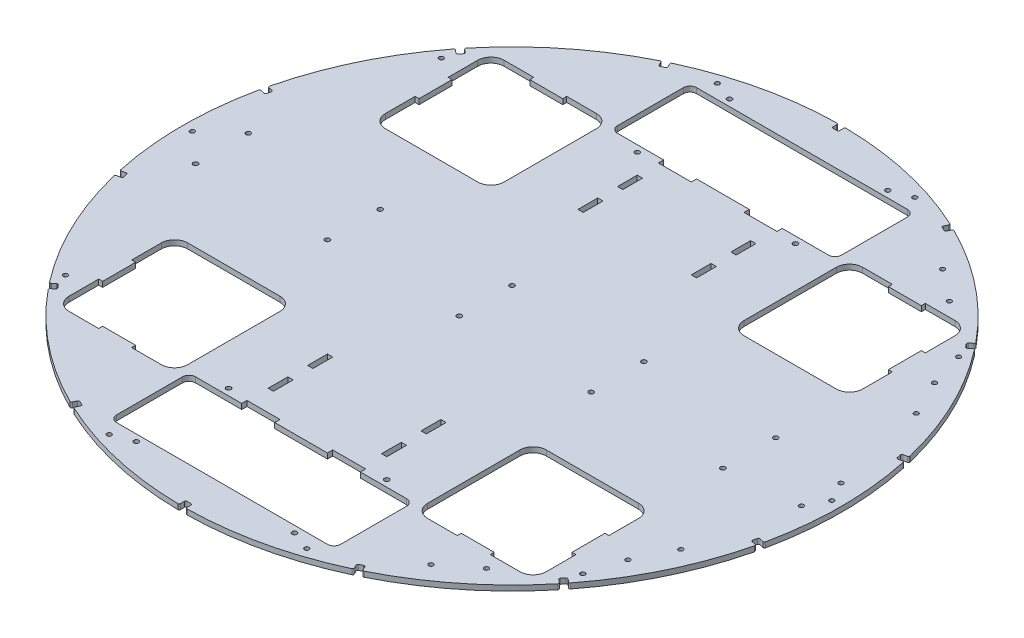
SolidWorks part; units mm, degrees
ref_plane "Front Plane" through (0, 0, 0) normal (0, 0, 1) x (1, 0, 0)
ref_plane "Top Plane" through (0, 0, 0) normal (0, 1, 0) x (1, 0, 0)
ref_plane "Right Plane" through (0, 0, 0) normal (1, 0, 0) x (0, 0, -1)
sketch "Sketch1" plane through (0, 0, 0) normal (0, 1, 0) x (1, 0, 0)
  circle A0 centre (0, 0) radius 250
extrude "Boss-Extrude1" add sketch "Sketch1" along normal blind 4
sketch "Sketch2" plane through (0, 4, 0) normal (0, 1, 0) x (1, 0, 0)
  line L0 (0, -250) -> (0, 250) construction
  line L1 (80, 220) -> (-80, 220)
  line L2 (85, 215) -> (85, 165)
  line L3 (80, 160) -> (-80, 160)
  line L4 (-85, 215) -> (-85, 165)
  line L5 (85, 220) -> (-85, 160) construction
  line L6 (85, 160) -> (-85, 220) construction
  line L7 (-55, 0) -> (55, 0) construction
  line L8 (85, -215) -> (85, -165)
  line L9 (80, -160) -> (-80, -160)
  line L10 (-85, -215) -> (-85, -165)
  line L11 (80, -220) -> (-80, -220)
  circle A0 centre (0, 0) radius 250 construction
  arc A1 (-80, 160) -> (-85, 165) centre (-80, 165) cw
  arc A2 (80, 160) -> (85, 165) centre (80, 165) ccw
  arc A3 (85, 215) -> (80, 220) centre (80, 215) ccw
  arc A4 (-80, 220) -> (-85, 215) centre (-80, 215) ccw
  arc A5 (-85, -215) -> (-80, -220) centre (-80, -215) ccw
  arc A6 (80, -220) -> (85, -215) centre (80, -215) ccw
  arc A7 (85, -165) -> (80, -160) centre (80, -165) ccw
  arc A8 (-80, -160) -> (-85, -165) centre (-80, -165) ccw
  point P0 (0, 190)
  point P33 (-85, -220)
  point P36 (85, -220)
  point P39 (85, -160)
  point P42 (-85, -160)
  dimension "D4" = 5
  dimension "D5" = 5
  dimension "D1" = 170
  dimension "D2" = 190
  dimension "D3" = 60
extrude "Cut-Extrude1" cut sketch "Sketch2" against normal blind 10
sketch "Sketch3" plane through (0, 4, 0) normal (0, 1, 0) x (1, 0, 0)
  line L0 (45, 160) -> (-45, 160)
  line L1 (-80, 160) -> (80, 160) construction
  line L2 (0, -2.2) -> (0, 2.2) construction
  line L3 (-45, 160) -> (-20, 160)
  line L4 (-45, 160) -> (-45, 156)
  line L5 (-45, 156) -> (-20, 156)
  line L6 (-20, 160) -> (-20, 156)
  line L7 (20, 160) -> (20, 156)
  line L8 (45, 156) -> (20, 156)
  line L9 (45, 160) -> (45, 156)
  line L10 (45, 160) -> (20, 160)
  line L11 (-2.2, 0) -> (2.2, 0) construction
  line L12 (45, -160) -> (20, -160)
  line L13 (45, -160) -> (45, -156)
  line L14 (45, -156) -> (20, -156)
  line L15 (20, -160) -> (20, -156)
  line L16 (-20, -160) -> (-20, -156)
  line L17 (-45, -156) -> (-20, -156)
  line L18 (-45, -160) -> (-45, -156)
  line L19 (-45, -160) -> (-20, -160)
  line L20 (45, -160) -> (-45, -160)
  point P5 (0, 160)
  point P24 (0, -160)
  line M7 (80, 160) -> (-80, 160)
  line M10 (-80, -160) -> (80, -160)
  dimension "D2" = 4
  dimension "D3" = 25
extrude "Cut-Extrude2" cut sketch "Sketch3" against normal blind 5 contours L6 L0 L4 L5 | L9 L7 L8 M7 | L18 L16 L17 M10 | L15 L13 L14 M10
sketch "Sketch4" plane through (0, 4, 0) normal (0, 1, 0) x (1, 0, 0)
  line L0 (45, 160) -> (-45, 160)
  line L3 (80, 220) -> (-80, 220) construction
  line L4 (45, 160) -> (80, 160) construction
  line L5 (45, 140) -> (41, 140)
  line L6 (45, 140) -> (45, 125)
  line L7 (45, 125) -> (41, 125)
  line L8 (41, 140) -> (41, 125)
  line L9 (0, -2.2) -> (0, 2.2) construction
  line L10 (41, 110) -> (45, 110)
  line L11 (41, 110) -> (41, 95)
  line L12 (41, 95) -> (45, 95)
  line L13 (45, 110) -> (45, 95)
  line L14 (-45, 110) -> (-45, 95)
  line L15 (-41, 95) -> (-45, 95)
  line L16 (-41, 110) -> (-41, 95)
  line L17 (-41, 110) -> (-45, 110)
  line L18 (-41, 140) -> (-41, 125)
  line L19 (-45, 125) -> (-41, 125)
  line L20 (-45, 140) -> (-45, 125)
  line L21 (-45, 140) -> (-41, 140)
  line L22 (-2.2, 0) -> (2.2, 0) construction
  line L23 (-45, -140) -> (-41, -140)
  line L24 (-45, -140) -> (-45, -125)
  line L25 (-45, -125) -> (-41, -125)
  line L26 (-41, -140) -> (-41, -125)
  line L27 (-41, -110) -> (-45, -110)
  line L28 (-41, -110) -> (-41, -95)
  line L29 (-41, -95) -> (-45, -95)
  line L30 (-45, -110) -> (-45, -95)
  line L31 (45, -110) -> (45, -95)
  line L32 (41, -95) -> (45, -95)
  line L33 (41, -110) -> (41, -95)
  line L34 (41, -110) -> (45, -110)
  line L35 (41, -140) -> (41, -125)
  line L36 (45, -125) -> (41, -125)
  line L37 (45, -140) -> (45, -125)
  line L38 (45, -140) -> (41, -140)
  point P3 (0, 160)
  point P5 (0, 220)
  point P16 (45, 132.5)
  point P17 (45, 102.5)
  dimension "D1" = 0
  dimension "D2" = 4
  dimension "D3" = 0
  dimension "D4" = 90
  dimension "D5" = 15
  dimension "D6" = 20
  dimension "D7" = 15
  dimension "D8" = 4
  dimension "D9" = 30
extrude "Cut-Extrude3" cut sketch "Sketch4" against normal blind 20 contours L5 L8 L7 L6 | L13 L10 L11 L12 | L21 L20 L19 L18 | L16 L17 L14 L15 | L30 L27 L28 L29 | L23 L26 L25 L24 | L33 L34 L31 L32 | L38 L37 L36 L35
sketch "Sketch7" plane through (0, 4, 0) normal (0, 1, 0) x (1, 0, 0)
  line L0 (0, -2.2) -> (0, 2.2) construction
  line L1 (-101, 75) -> (-171, 75)
  line L2 (-91, 85) -> (-91, 155)
  line L3 (-101, 165) -> (-171, 165)
  line L4 (-181, 85) -> (-181, 155)
  line L5 (-91, 75) -> (-181, 165) construction
  line L6 (-91, 165) -> (-181, 75) construction
  line L7 (91, 165) -> (181, 75) construction
  line L8 (91, 75) -> (181, 165) construction
  line L9 (181, 85) -> (181, 155)
  line L10 (101, 165) -> (171, 165)
  line L11 (91, 85) -> (91, 155)
  line L12 (101, 75) -> (171, 75)
  line L13 (-2.2, 0) -> (2.2, 0) construction
  line L14 (91, -75) -> (181, -165) construction
  line L15 (91, -165) -> (181, -75) construction
  line L16 (101, -75) -> (171, -75)
  line L17 (91, -85) -> (91, -155)
  line L18 (101, -165) -> (171, -165)
  line L19 (181, -85) -> (181, -155)
  line L20 (-91, -165) -> (-181, -75) construction
  line L21 (-91, -75) -> (-181, -165) construction
  line L22 (-181, -85) -> (-181, -155)
  line L23 (-101, -165) -> (-171, -165)
  line L24 (-91, -85) -> (-91, -155)
  line L25 (-101, -75) -> (-171, -75)
  arc A0 (-171, 165) -> (-181, 155) centre (-171, 155) ccw
  arc A1 (-91, 155) -> (-101, 165) centre (-101, 155) ccw
  arc A2 (-181, -155) -> (-171, -165) centre (-171, -155) ccw
  arc A3 (-101, -165) -> (-91, -155) centre (-101, -155) ccw
  arc A4 (-91, -85) -> (-101, -75) centre (-101, -85) ccw
  arc A5 (-171, -75) -> (-181, -85) centre (-171, -85) ccw
  arc A6 (91, -155) -> (101, -165) centre (101, -155) ccw
  arc A7 (171, -165) -> (181, -155) centre (171, -155) ccw
  arc A8 (181, -85) -> (171, -75) centre (171, -85) ccw
  arc A9 (101, -75) -> (91, -85) centre (101, -85) ccw
  arc A10 (101, 75) -> (91, 85) centre (101, 85) cw
  arc A11 (171, 75) -> (181, 85) centre (171, 85) ccw
  arc A12 (181, 155) -> (171, 165) centre (171, 155) ccw
  arc A13 (91, 155) -> (101, 165) centre (101, 155) cw
  arc A14 (-171, 75) -> (-181, 85) centre (-171, 85) cw
  arc A15 (-101, 75) -> (-91, 85) centre (-101, 85) ccw
  point P0 (-136, 120)
  point P12 (136, 120)
  point P19 (136, -120)
  point P24 (-136, -120)
  dimension "D5" = 10
  dimension "D6" = 10
  dimension "D7" = 10
  dimension "D1" = 90
  dimension "D2" = 90
  dimension "D3" = 136
  dimension "D4" = 120
extrude "Cut-Extrude4" cut sketch "Sketch7" against normal blind 5
sketch "Sketch8" plane through (0, 4, 0) normal (0, 1, 0) x (1, 0, 0)
  line L0 (-181, 155) -> (-181, 85) construction
  line L1 (-178, 107.5) -> (-184, 107.5)
  line L2 (-178, 107.5) -> (-178, 132.5)
  line L3 (-178, 132.5) -> (-184, 132.5)
  line L4 (-184, 107.5) -> (-184, 132.5)
  line L5 (-178, 107.5) -> (-184, 132.5) construction
  line L6 (-178, 132.5) -> (-184, 107.5) construction
  line L7 (-101, 165) -> (-171, 165) construction
  line L8 (-123.5, 162) -> (-148.5, 162)
  line L9 (-123.5, 162) -> (-123.5, 168)
  line L10 (-123.5, 168) -> (-148.5, 168)
  line L11 (-148.5, 162) -> (-148.5, 168)
  line L12 (-123.5, 162) -> (-148.5, 168) construction
  line L13 (-123.5, 168) -> (-148.5, 162) construction
  line L14 (0, -2.2) -> (0, 2.2) construction
  line L15 (123.5, 168) -> (148.5, 162) construction
  line L16 (123.5, 162) -> (148.5, 168) construction
  line L17 (178, 132.5) -> (184, 107.5) construction
  line L18 (178, 107.5) -> (184, 132.5) construction
  line L19 (148.5, 162) -> (148.5, 168)
  line L20 (123.5, 168) -> (148.5, 168)
  line L21 (123.5, 162) -> (123.5, 168)
  line L22 (123.5, 162) -> (148.5, 162)
  line L23 (184, 107.5) -> (184, 132.5)
  line L24 (178, 132.5) -> (184, 132.5)
  line L25 (178, 107.5) -> (178, 132.5)
  line L26 (178, 107.5) -> (184, 107.5)
  line L27 (-2.2, 0) -> (2.2, 0) construction
  line L28 (178, -107.5) -> (184, -132.5) construction
  line L29 (178, -132.5) -> (184, -107.5) construction
  line L30 (123.5, -162) -> (148.5, -168) construction
  line L31 (123.5, -168) -> (148.5, -162) construction
  line L32 (178, -107.5) -> (184, -107.5)
  line L33 (178, -107.5) -> (178, -132.5)
  line L34 (178, -132.5) -> (184, -132.5)
  line L35 (184, -107.5) -> (184, -132.5)
  line L36 (123.5, -162) -> (148.5, -162)
  line L37 (123.5, -162) -> (123.5, -168)
  line L38 (123.5, -168) -> (148.5, -168)
  line L39 (148.5, -162) -> (148.5, -168)
  line L40 (-123.5, -168) -> (-148.5, -162) construction
  line L41 (-123.5, -162) -> (-148.5, -168) construction
  line L42 (-178, -132.5) -> (-184, -107.5) construction
  line L43 (-178, -107.5) -> (-184, -132.5) construction
  line L44 (-148.5, -162) -> (-148.5, -168)
  line L45 (-123.5, -168) -> (-148.5, -168)
  line L46 (-123.5, -162) -> (-123.5, -168)
  line L47 (-123.5, -162) -> (-148.5, -162)
  line L48 (-184, -107.5) -> (-184, -132.5)
  line L49 (-178, -132.5) -> (-184, -132.5)
  line L50 (-178, -107.5) -> (-178, -132.5)
  line L51 (-178, -107.5) -> (-184, -107.5)
  point P0 (-181, 120)
  point P7 (-136, 165)
  point P24 (136, 165)
  point P25 (181, 120)
  point P36 (181, -120)
  point P37 (136, -165)
  point P46 (-136, -165)
  point P47 (-181, -120)
  dimension "D1" = 6
  dimension "D2" = 25
  dimension "D3" = 6
  dimension "D4" = 25
extrude "Boss-Extrude2" add sketch "Sketch8" against normal blind 4
sketch "Sketch11" plane through (0, 4, 0) normal (0, 1, 0) x (1, 0, 0)
  line L1 (1.5, 245) -> (-1.5, 245)
  line L2 (2.5, 246) -> (2.5, 255)
  line L3 (2.5, 255) -> (-2.5, 255)
  line L4 (-2.5, 246) -> (-2.5, 255)
  line L5 (2.5, 245) -> (-2.5, 255) construction
  line L6 (2.5, 255) -> (-2.5, 245) construction
  circle A0 centre (0, 0) radius 250 construction
  arc A1 (2.5, 246) -> (1.5, 245) centre (1.5, 246) cw
  arc A2 (-1.5, 245) -> (-2.5, 246) centre (-1.5, 246) cw
  point P0 (0, 250)
  dimension "D3" = 1
  dimension "D1" = 10
  dimension "D2" = 5
extrude "Cut-Extrude5" cut sketch "Sketch11" against normal blind 4
fillet "Fillet1" radius 1 2 edges at (2.5, 2, -249.9875) (-2.5, 2, -249.9875)
pattern_circular "CirPattern1" count 14 over 360 about axis through (0, 0, 0) along (0, 1, 0) of "Cut-Extrude5", "Fillet1"
sketch "Sketch12" plane through (0, 4, 0) normal (0, 1, 0) x (1, 0, 0)
  circle A1 centre (0, 0) radius 242.5
  circle A3 centre (-242.5, 0) radius 1.7
  dimension "D2" = 485
extrude "Cut-Extrude6" cut sketch "Sketch12" against normal blind 10 contours A1 A3 | A1 A3
pattern_circular "CirPattern2" count 10 over 360 about axis through (0, 0, 0) along (0, 1, 0) of "Cut-Extrude6"
sketch "Sketch13" plane through (0, 4, 0) normal (0, 1, 0) x (1, 0, 0)
  line L0 (-2.2, 0) -> (2.2, 0) construction
  line L1 (0, 0) -> (234.5, -15) construction
  line L2 (0, 0) -> (204.1916, -116.2799) construction
  line L3 (0, 0) -> (234.5, -15) construction
  line L4 (0, 0) -> (217.3428, 89.3161) construction
  circle A0 centre (234.5, 15) radius 1.7
  circle A1 centre (242.5, 0) radius 1.7 construction
  circle A2 centre (234.5, -15) radius 1.7
  circle A3 centre (217.3428, -89.3161) radius 1.7
  circle A4 centre (204.1916, -116.2799) radius 1.7
  circle A5 centre (156.1928, -175.5536) radius 1.7
  circle A6 centre (132.5525, -194.0234) radius 1.7
  circle A7 centre (204.1916, 116.2799) radius 1.7
  circle A8 centre (217.3428, 89.3161) radius 1.7
  circle A9 centre (132.5525, 194.0234) radius 1.7
  circle A10 centre (156.1928, 175.5536) radius 1.7
  dimension "D1" = 15
  dimension "D2" = 8
  dimension "D4" = 26
  dimension "D6" = 26
  dimension "D3" = 3
  dimension "D5" = 3
extrude "Cut-Extrude7" cut sketch "Sketch13" against normal blind 10
sketch "Sketch14" plane through (0, 4, 0) normal (0, 1, 0) x (1, 0, 0)
  line L0 (-2.2, 0) -> (2.2, 0) construction
  circle A0 centre (-220, 20) radius 1.8
  circle A1 centre (-220, -20) radius 1.8
  circle A2 centre (-120, 20) radius 1.8
  circle A3 centre (-120, -20) radius 1.8
  circle A4 centre (-20, 20) radius 1.8
  circle A5 centre (-20, -20) radius 1.8
  circle A6 centre (80, 20) radius 1.8
  circle A7 centre (80, -20) radius 1.8
  circle A8 centre (180, 20) radius 1.8
  circle A9 centre (180, -20) radius 1.8
  dimension "D1" = 220
  dimension "D2" = 20
  dimension "D3" = 5
extrude "Cut-Extrude8" cut sketch "Sketch14" against normal blind 10
sketch "Sketch15" plane through (0, 4, 0) normal (0, 1, 0) x (1, 0, 0)
  line L0 (-80, -220) -> (80, -220) construction
  line L1 (20, -160) -> (-20, -160) construction
  line L2 (0, -2.2) -> (0, 2.2) construction
  line L3 (-2.2, 0) -> (2.2, 0) construction
  circle A0 centre (-60, -225) radius 1.8
  circle A1 centre (60, -225) radius 1.8
  circle A2 centre (-60, -155) radius 1.8
  circle A3 centre (60, -155) radius 1.8
  circle A4 centre (60, 155) radius 1.8
  circle A5 centre (-60, 155) radius 1.8
  circle A6 centre (60, 225) radius 1.8
  circle A7 centre (-60, 225) radius 1.8
  point P6 (0, -160)
  dimension "D1" = 5
  dimension "D2" = 60
  dimension "D3" = 2
extrude "Cut-Extrude9" cut sketch "Sketch15" against normal blind 10
